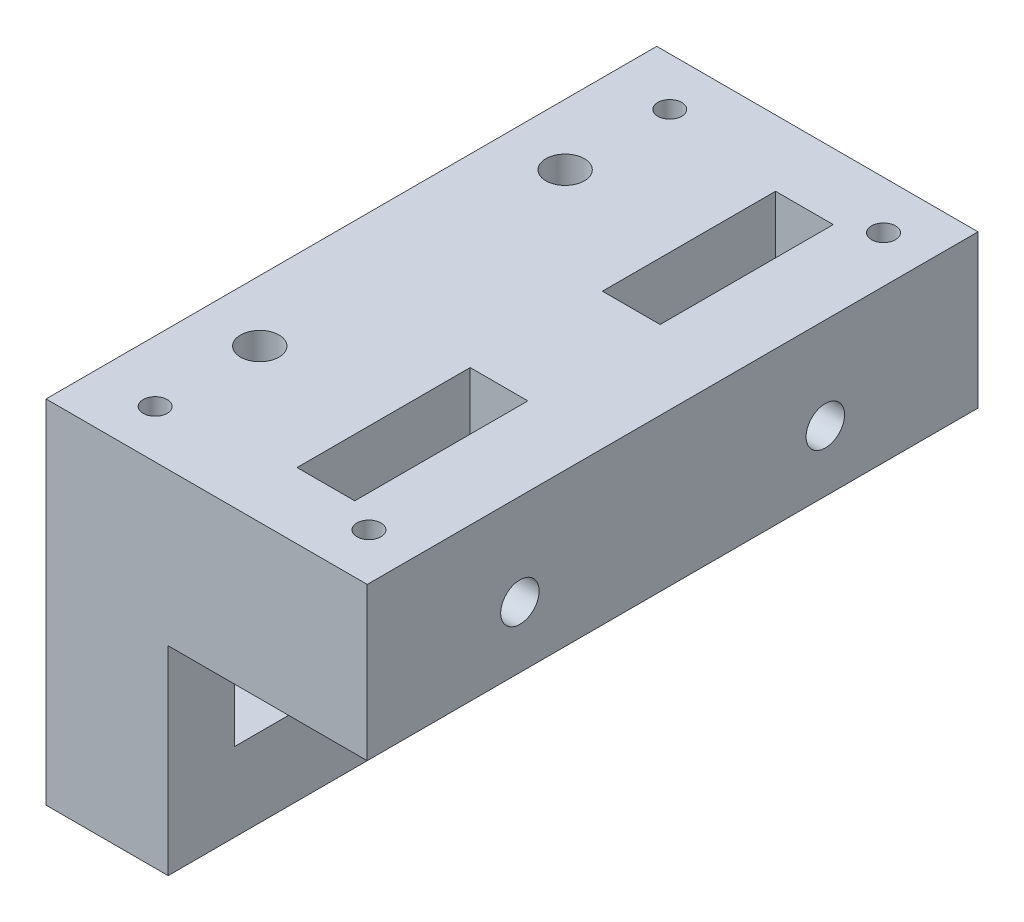
SolidWorks part; units mm, degrees
ref_plane "Front Plane" through (0, 0, 0) normal (0, 0, 1) x (1, 0, 0)
ref_plane "Top Plane" through (0, 0, 0) normal (0, 1, 0) x (1, 0, 0)
ref_plane "Right Plane" through (0, 0, 0) normal (1, 0, 0) x (0, 0, -1)
sketch "Sketch1" plane through (0, 0, 0) normal (0, 1, 0) x (1, 0, 0)
  line L1 (-22.225, -31.75) -> (22.225, -31.75)
  line L2 (-22.225, -31.75) -> (-22.225, 31.75)
  line L3 (-22.225, 31.75) -> (22.225, 31.75)
  line L4 (22.225, -31.75) -> (22.225, 31.75)
  line L5 (-22.225, -31.75) -> (22.225, 31.75) construction
  line L6 (-22.225, 31.75) -> (22.225, -31.75) construction
  line L7 (0, 31.75) -> (0, 0)
  line L8 (0, 0) -> (0, -31.75)
  line L9 (-3, 24.875) -> (3, 24.875)
  line L10 (-3, 24.875) -> (-3, 6.875)
  line L11 (-3, 6.875) -> (3, 6.875)
  line L12 (3, 24.875) -> (3, 6.875)
  line L13 (-3, 24.875) -> (3, 6.875) construction
  line L14 (-3, 6.875) -> (3, 24.875) construction
  line L15 (-3, -6.875) -> (3, -6.875)
  line L16 (-3, -6.875) -> (-3, -24.875)
  line L17 (-3, -24.875) -> (3, -24.875)
  line L18 (3, -6.875) -> (3, -24.875)
  line L19 (-3, -6.875) -> (3, -24.875) construction
  line L20 (-3, -24.875) -> (3, -6.875) construction
  point P0 (0, 0)
  point P8 (0, 15.875)
  point P14 (0, -15.875)
  dimension "D1" = 44.45
  dimension "D2" = 63.5
  dimension "D3" = 18
  dimension "D4" = 18
  dimension "D5" = 6
  dimension "D6" = 6
extrude "Boss-Extrude1" add sketch "Sketch1" along normal blind 12.7 contours L17 L16 L15 L8 L7 L11 L10 L9 L3 L2 L1 | L15 L18 L17 L8 L1 L4 L3 L7 L9 L12 L11
sketch "Sketch2" plane through (0, 0, 0) normal (0, -1, 0) x (1, 0, 0)
  line L0 (-22.225, -31.75) -> (22.225, -31.75) construction
  line L1 (-22.225, 31.75) -> (-9.525, 31.75)
  line L2 (-22.225, 31.75) -> (-22.225, -31.75)
  line L3 (-22.225, -31.75) -> (-9.525, -31.75)
  line L4 (-9.525, 31.75) -> (-9.525, -31.75)
  dimension "D1" = 12.7
extrude "Boss-Extrude2" add sketch "Sketch2" along normal blind 31.75
sketch "Sketch3" plane through (-22.225, 0, 0) normal (-1, 0, 0) x (0, 0, 1)
  line L0 (-31.75, -9.525) -> (0, -9.525)
  line L1 (-31.75, 12.7) -> (-31.75, -31.75) construction
  line L2 (0, -9.525) -> (31.75, -9.525)
  line L3 (31.75, 12.7) -> (31.75, -31.75) construction
  line L5 (-24.875, -6.525) -> (-6.875, -6.525)
  line L6 (-24.875, -6.525) -> (-24.875, -12.525)
  line L7 (-24.875, -12.525) -> (-6.875, -12.525)
  line L8 (-6.875, -6.525) -> (-6.875, -12.525)
  line L9 (-24.875, -6.525) -> (-6.875, -12.525) construction
  line L10 (-24.875, -12.525) -> (-6.875, -6.525) construction
  line L11 (6.875, -6.525) -> (24.875, -6.525)
  line L12 (6.875, -6.525) -> (6.875, -12.525)
  line L13 (6.875, -12.525) -> (24.875, -12.525)
  line L14 (24.875, -6.525) -> (24.875, -12.525)
  line L15 (6.875, -6.525) -> (24.875, -12.525) construction
  line L16 (6.875, -12.525) -> (24.875, -6.525) construction
  point P4 (-15.875, -9.525)
  point P12 (15.875, -9.525)
  dimension "D1" = 6
  dimension "D2" = 6
  dimension "D3" = 18
  dimension "D5" = 18
extrude "Cut-Extrude1" cut sketch "Sketch3" against normal blind 19.05 contours L8 L5 L6 L0 | L8 L0 L6 L7 | L14 L11 L12 L2 | L14 L2 L12 L13
sketch "Sketch4" plane through (0, 12.7, 0) normal (0, 1, 0) x (1, 0, 0)
  line L0 (-22.225, 31.75) -> (-15.875, 31.75)
  line L1 (-22.225, 31.75) -> (22.225, 31.75) construction
  line L2 (-15.875, 31.75) -> (-15.875, 15.875)
  line L3 (-15.875, 15.875) -> (-15.875, -15.875)
  circle A0 centre (-15.875, 15.875) radius 2
  circle A1 centre (-15.875, -15.875) radius 2
  dimension "D1" = 6.35
  dimension "D2" = 15.875
  dimension "D3" = 31.75
extrude "Cut-Extrude2" cut sketch "Sketch4" against normal through all
sketch "Sketch5" plane through (-22.225, 0, 0) normal (-1, 0, 0) x (0, 0, 1)
  line L0 (-31.75, 12.7) -> (-31.75, 6.35)
  line L1 (-31.75, 12.7) -> (-31.75, -31.75) construction
  line L2 (-31.75, 6.35) -> (-15.875, 6.35)
  line L3 (-15.875, 6.35) -> (15.875, 6.35)
  circle A0 centre (-15.875, 6.35) radius 2
  circle A1 centre (15.875, 6.35) radius 2
  dimension "D1" = 6.35
  dimension "D2" = 31.75
  dimension "D3" = 15.875
extrude "Cut-Extrude3" cut sketch "Sketch5" against normal through all
sketch "Sketch6" plane through (22.225, 0, 0) normal (1, 0, 0) x (0, 0, -1)
  line L1 (-31.75, 12.7) -> (31.75, 12.7)
  line L2 (-31.75, 12.7) -> (-31.75, 0)
  line L3 (-31.75, 0) -> (31.75, 0)
  line L4 (31.75, 12.7) -> (31.75, 0)
extrude "Cut-Extrude4" cut sketch "Sketch6" against normal blind 11.05
sketch "Sketch7" plane through (0, -31.75, 0) normal (0, -1, 0) x (1, 0, 0)
  line L1 (-22.225, 31.75) -> (-9.525, 31.75)
  line L2 (-22.225, 31.75) -> (-22.225, -31.75)
  line L3 (-22.225, -31.75) -> (-9.525, -31.75)
  line L4 (-9.525, 31.75) -> (-9.525, -31.75)
extrude "Cut-Extrude5" cut sketch "Sketch7" against normal blind 11.05
sketch "Sketch8" plane through (0, 12.7, 0) normal (0, 1, 0) x (1, 0, 0)
  line L1 (-22.225, 31.75) -> (11.175, 31.75)
  line L2 (-22.225, 31.75) -> (-22.225, -31.75)
  line L3 (-22.225, -31.75) -> (11.175, -31.75)
  line L4 (11.175, 31.75) -> (11.175, -31.75)
  line L5 (3, -24.875) -> (-3, -24.875)
  line L6 (3, -24.875) -> (3, -6.875)
  line L7 (3, -6.875) -> (-3, -6.875)
  line L8 (-3, -24.875) -> (-3, -6.875)
  line L9 (-3, 6.875) -> (3, 6.875)
  line L10 (-3, 6.875) -> (-3, 24.875)
  line L11 (-3, 24.875) -> (3, 24.875)
  line L12 (3, 6.875) -> (3, 24.875)
  circle A0 centre (-15.875, 15.875) radius 2
  circle A1 centre (-15.875, -15.875) radius 2
extrude "Boss-Extrude3" add sketch "Sketch8" along normal blind 3.175
sketch "Sketch9" plane through (0, 15.875, 0) normal (0, 1, 0) x (1, 0, 0)
  line L0 (-15.875, 31.75) -> (-22.225, 31.75)
  line L2 (-22.225, 31.75) -> (-15.875, 31.75)
  line L3 (-15.875, 31.75) -> (-15.875, 26.75)
  line L4 (-22.225, -31.75) -> (-15.875, -31.75)
  line L5 (-22.225, -31.75) -> (11.175, -31.75) construction
  line L6 (-15.875, -31.75) -> (-15.875, -26.75)
  line L7 (-15.875, -26.75) -> (6.35, -26.75)
  line L8 (-15.875, 26.75) -> (6.35, 26.75)
  circle A0 centre (-15.875, 26.75) radius 1.25
  circle A1 centre (-15.875, -26.75) radius 1.25
  circle A2 centre (6.35, 26.75) radius 1.25
  circle A3 centre (6.35, -26.75) radius 1.25
  dimension "D3" = 5
  dimension "D4" = 22.225
  dimension "D1" = 5
  dimension "D2" = 6.35
  dimension "D5" = 22.225
extrude "Cut-Extrude6" cut sketch "Sketch9" against normal blind 12.7 contours A0 | A2 | A1 | A3
